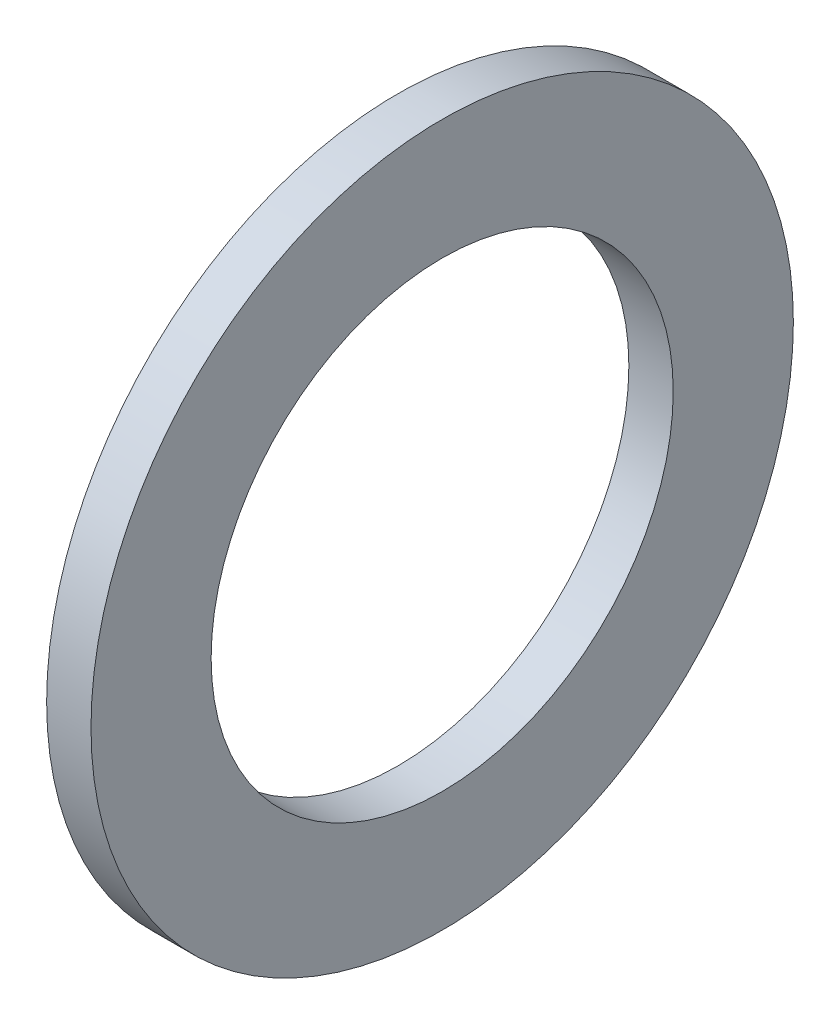
SolidWorks part; units mm, degrees
ref_plane "Front Plane" through (0, 0, 0) normal (0, 0, 1) x (1, 0, 0)
ref_plane "Top Plane" through (0, 0, 0) normal (0, 1, 0) x (1, 0, 0)
ref_plane "Right Plane" through (0, 0, 0) normal (1, 0, 0) x (0, 0, -1)
sketch "Sketch1" plane through (0, 0, 0) normal (1, 0, 0) x (0, 0, -1)
  circle A0 centre (0, 0) radius 7.239
  circle A1 centre (0, 0) radius 4.7625
  dimension "OD" = 14.478
  dimension "ID" = 9.525
extrude "Boss-Extrude1" add sketch "Sketch1" along normal blind 0.9144
